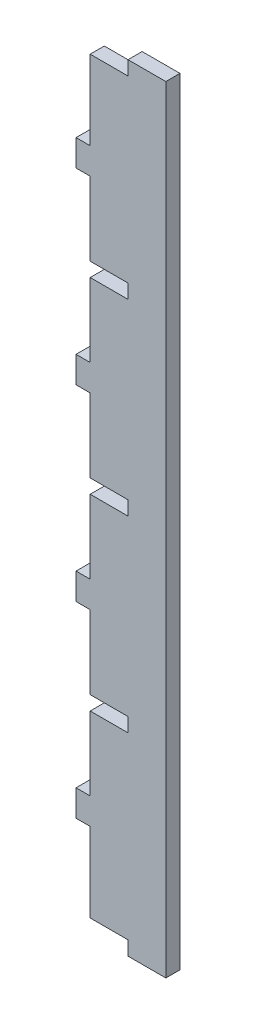
SolidWorks part; units mm, degrees
ref_plane "Front Plane" through (0, 0, 0) normal (0, 0, 1) x (1, 0, 0)
ref_plane "Top Plane" through (0, 0, 0) normal (0, 1, 0) x (1, 0, 0)
ref_plane "Right Plane" through (0, 0, 0) normal (1, 0, 0) x (0, 0, -1)
sketch "Model" plane through (0, 0, 0) normal (0, 0, 1) x (1, 0, 0)
  line L132 (19.675, 5.35) -> (19.675, 0)
  line L133 (5.35, 5.35) -> (19.675, 5.35)
  line L134 (5.35, 35.382) -> (5.35, 5.35)
  line L135 (0, 35.382) -> (5.35, 35.382)
  line L136 (0, 45.382) -> (0, 35.382)
  line L137 (5.35, 45.382) -> (0, 45.382)
  line L138 (5.35, 73.2463) -> (5.35, 45.382)
  line L139 (19.675, 73.2463) -> (5.35, 73.2463)
  line L140 (19.675, 78.5963) -> (19.675, 73.2463)
  line L141 (5.35, 78.5963) -> (19.675, 78.5963)
  line L142 (5.35, 106.4607) -> (5.35, 78.5963)
  line L143 (0, 106.4607) -> (5.35, 106.4607)
  line L144 (0, 116.4607) -> (0, 106.4607)
  line L145 (5.35, 116.4607) -> (0, 116.4607)
  line L146 (5.35, 144.325) -> (5.35, 116.4607)
  line L147 (19.675, 144.325) -> (5.35, 144.325)
  line L148 (19.675, 149.675) -> (19.675, 144.325)
  line L149 (5.35, 149.675) -> (19.675, 149.675)
  line L150 (5.35, 177.5393) -> (5.35, 149.675)
  line L151 (0, 177.5393) -> (5.35, 177.5393)
  line L152 (0, 187.5393) -> (0, 177.5393)
  line L153 (5.35, 187.5393) -> (0, 187.5393)
  line L154 (5.35, 215.4037) -> (5.35, 187.5393)
  line L155 (19.675, 215.4037) -> (5.35, 215.4037)
  line L156 (19.675, 220.7537) -> (19.675, 215.4037)
  line L157 (5.35, 220.7537) -> (19.675, 220.7537)
  line L158 (5.35, 248.618) -> (5.35, 220.7537)
  line L159 (0, 248.618) -> (5.35, 248.618)
  line L160 (0, 258.618) -> (0, 248.618)
  line L161 (5.35, 258.618) -> (0, 258.618)
  line L162 (5.35, 288.65) -> (5.35, 258.618)
  line L163 (19.675, 288.65) -> (5.35, 288.65)
  line L164 (19.675, 294) -> (19.675, 288.65)
  line L165 (34, 294) -> (19.675, 294)
  line L166 (34, 0) -> (34, 294)
  line L167 (19.675, 0) -> (34, 0)
extrude "Boss-Extrude1" add sketch "Model" along normal blind 5.35
